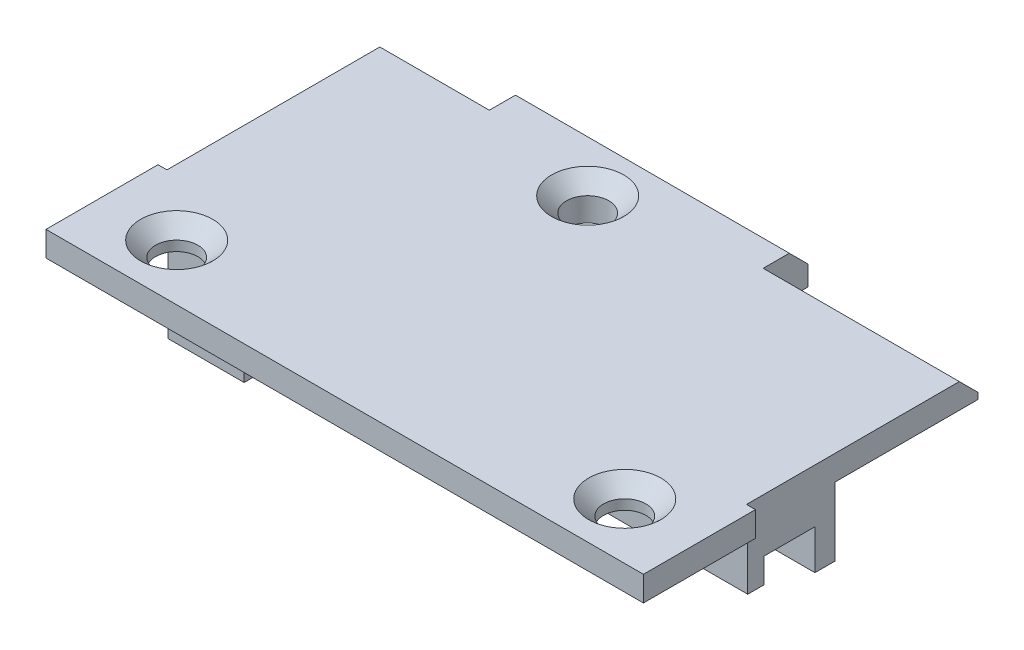
SolidWorks part; units mm, degrees
ref_plane "Front Plane" through (0, 0, 0) normal (0, 0, 1) x (1, 0, 0)
ref_plane "Top Plane" through (0, 0, 0) normal (0, 1, 0) x (1, 0, 0)
ref_plane "Right Plane" through (0, 0, 0) normal (1, 0, 0) x (0, 0, -1)
sketch "Sketch1" plane through (0, 0, 0) normal (0, 1, 0) x (1, 0, 0)
  line L0 (0, 0) -> (0, 9)
  line L1 (0, 9) -> (0.72, 9)
  line L2 (0.72, 9) -> (0.72, 27.6)
  line L3 (0.72, 27.6) -> (9.52, 27.6)
  line L4 (9.52, 27.6) -> (9.52, 29.7)
  line L5 (9.52, 29.7) -> (31.52, 29.7)
  line L6 (31.52, 29.7) -> (31.52, 27.6)
  line L7 (31.52, 27.6) -> (47.28, 27.6)
  line L8 (47.28, 27.6) -> (47.28, 9)
  line L9 (47.28, 9) -> (48, 9)
  line L10 (48, 9) -> (48, 0)
  line L11 (48, 0) -> (0, 0)
  circle A0 centre (19.42, 24.1) radius 1.7
  circle A1 centre (6, 4.5) radius 1.7
  circle A2 centre (42, 4.5) radius 1.7
  dimension "D8" = 3.4
  dimension "D1" = 48
  dimension "D2" = 9
  dimension "D3" = 0.72
  dimension "D4" = 18.6
  dimension "D5" = 2.1
  dimension "D6" = 22
  dimension "D7" = 15.76
  dimension "D9" = 24.1
  dimension "D10" = 19.42
  dimension "D11" = 4.5
  dimension "D12" = 6
  dimension "D13" = 6
  dimension "D14" = 4.5
extrude "Boss-Extrude1" add sketch "Sketch1" against normal blind 2
chamfer "Chamfer1" distance 1.5 angle 45 3 edges at (5.12, 0, -27.6) (20.52, 0, -29.7) (39.4, 0, -27.6)
chamfer "Chamfer2" distance 1.2 angle 45 3 edges at (6, 0, -2.8) (19.42, 0, -22.4) (42, 0, -2.8)
sketch "Sketch2" plane through (0, -2, 0) normal (0, -1, 0) x (1, 0, 0)
  line L0 (9.52, -28) -> (31.52, -28)
  line L1 (9.52, -29.7) -> (31.52, -29.7)
  line L2 (9.52, -29.7) -> (9.52, -28)
  line L5 (31.52, -28) -> (31.52, -29.7)
  dimension "D1" = 1.7
extrude "Boss-Extrude2" add sketch "Sketch2" along normal blind 1.1
sketch "Sketch3" plane through (0, -2, 0) normal (0, -1, 0) x (1, 0, 0)
  line L0 (19.42, -21) -> (19.42, -28) construction
  line L2 (12.42, -28) -> (12.42, -21)
  line L3 (12.42, -21) -> (26.42, -21)
  line L4 (26.42, -28) -> (26.42, -21)
  line L12 (31.52, -28) -> (9.52, -28) construction
  line L14 (12.42, -28) -> (26.42, -28)
  circle A0 centre (19.42, -24.1) radius 1.7
  circle A1 centre (19.42, -24.1) radius 1.7 construction
  dimension "D1" = 14
  dimension "D3" = 7
extrude "Boss-Extrude3" add sketch "Sketch3" along normal up to surface (1.1 mm away) up to face at (20.52, -3.1, -28.85)
sketch "Sketch4" plane through (0, -2, 0) normal (0, -1, 0) x (1, 0, 0)
  line L0 (0.72, -9.1) -> (47.28, -9.1)
  line L1 (47.28, -9.1) -> (47.28, -16.1)
  line L2 (47.28, -9) -> (47.28, -27.6) construction
  line L3 (47.28, -16.3) -> (44.08, -16.3) construction
  line L4 (44.08, -16.3) -> (44.08, -18.2)
  line L5 (44.08, -18.2) -> (42.26, -18.2)
  line L6 (42.26, -18.2) -> (42.26, -16)
  line L7 (42.26, -16) -> (38.56, -16)
  line L8 (38.56, -16) -> (38.56, -18.2)
  line L9 (38.56, -18.2) -> (35.18, -18.2)
  line L10 (35.18, -18.2) -> (35.18, -16)
  line L11 (35.18, -16) -> (31.48, -16)
  line L12 (31.48, -16) -> (31.48, -18.2)
  line L13 (31.48, -18.2) -> (30.28, -18.2)
  line L14 (30.28, -18.2) -> (30.28, -14.4)
  line L15 (30.28, -14.4) -> (26.6, -14.4)
  line L16 (26.6, -14.4) -> (26.6, -13.4)
  line L17 (26.6, -13.4) -> (11.4, -13.4)
  line L18 (11.4, -13.4) -> (11.4, -18.2)
  line L19 (11.4, -18.2) -> (10.02, -18.2)
  line L20 (10.02, -18.2) -> (10.02, -16)
  line L21 (10.02, -16) -> (6.32, -16)
  line L22 (6.32, -16) -> (6.32, -18.2)
  line L23 (6.32, -18.2) -> (3.72, -18.2)
  line L24 (3.72, -18.2) -> (3.72, -19.4)
  line L25 (3.72, -19.4) -> (0.72, -19.4)
  line L26 (0.72, -27.6) -> (0.72, -9) construction
  line L27 (0.72, -19.4) -> (0.72, -9.1)
  line L28 (47.28, -16.1) -> (44.08, -16.1)
  line L29 (44.08, -16.1) -> (44.08, -16.3)
  line L30 (48, -9) -> (47.28, -9) construction
  dimension "D1" = 3
  dimension "D2" = 2.6
  dimension "D3" = 3.7
  dimension "D4" = 1.38
  dimension "D5" = 15.2
  dimension "D6" = 20.68
  dimension "D7" = 3.7
  dimension "D8" = 3.7
  dimension "D9" = 3.2
  dimension "D10" = 1.2
  dimension "D11" = 3.38
  dimension "D12" = 0.1
  dimension "D13" = 1.9
  dimension "D14" = 3.8
  dimension "D15" = 1
  dimension "D16" = 4.8
  dimension "D17" = 2.2
  dimension "D18" = 1.2
  dimension "D19" = 0.2
  dimension "D20" = 7
  dimension "D21" = 5.02
  dimension "D22" = 2.2
  dimension "D23" = 2.2
extrude "Boss-Extrude4" add sketch "Sketch4" along normal blind 5.5
fillet "Fillet1" radius 0.5 12 edges at (42.26, -4.75, -18.2) (42.26, -4.75, -16) (35.18, -4.75, -18.2) (35.18, -4.75, -16) (38.56, -4.75, -16) (38.56, -4.75, -18.2) (31.48, -4.75, -16) (31.48, -4.75, -18.2) (10.02, -4.75, -18.2) (10.02, -4.75, -16) (6.32, -4.75, -16) (6.32, -4.75, -18.2)
sketch "Sketch5" plane through (0, -7.5, 0) normal (0, -1, 0) x (1, 0, 0)
  line L0 (0.72, -9) -> (0, -9) construction
  line L1 (0.72, -9.1) -> (6.82, -9.1)
  line L2 (0.72, -9.1) -> (0.72, -14.5)
  line L3 (0.72, -14.5) -> (6.82, -14.5)
  line L4 (6.82, -9.1) -> (6.82, -14.5)
  line L5 (47.28, -9.1) -> (0.72, -9.1) construction
  line L6 (0.72, -9.1) -> (0.72, -19.4) construction
  dimension "D1" = 5.5
  dimension "D2" = 6.1
extrude "Boss-Extrude5" add sketch "Sketch5" along normal blind 4.3
sketch "Sketch6" plane through (0, -7.5, 0) normal (0, -1, 0) x (1, 0, 0)
  line L0 (47.28, -16.1) -> (47.28, -9.1) construction
  line L1 (6.82, -9.1) -> (47.28, -9.1)
  line L2 (6.82, -9.1) -> (6.82, -14.5)
  line L3 (6.82, -14.5) -> (47.28, -14.5)
  line L4 (47.28, -9.1) -> (47.28, -14.5)
  line L5 (0.72, -14.5) -> (6.82, -14.5) construction
extrude "Cut-Extrude1" cut sketch "Sketch6" against normal blind 1.2
sketch "Sketch7" plane through (0, -6.3, 0) normal (0, -1, 0) x (1, 0, 0)
  line L0 (11.4, -13.4) -> (11.4, -13.12)
  line L1 (12.14, -12.15) -> (14.52, -11.4893)
  line L2 (23.64, -10.4) -> (47.28, -10.4)
  line L3 (47.28, -14.5) -> (47.28, -9.1) construction
  line L4 (47.28, -10.4) -> (47.28, -14.5)
  line L5 (47.28, -14.5) -> (26.6, -14.5)
  line L6 (26.6, -14.5) -> (26.6, -13.4)
  line L7 (26.6, -13.4) -> (11.4, -13.4)
  arc A0 (11.4, -13.12) -> (12.14, -12.15) centre (12.4, -13.1156) cw
  arc A1 (14.52, -11.4893) -> (23.64, -10.4) centre (23.1951, -45.3972) cw
  dimension "D5" = 1
  dimension "D6" = 35
  dimension "D1" = 23.64
  dimension "D2" = 4.1
  dimension "D3" = 0.28
  dimension "D4" = 2.47
  dimension "D7" = 0.97
  dimension "D8" = 0.74
  dimension "D9" = 2.38
extrude "Cut-Extrude2" cut sketch "Sketch7" against normal blind 2
sketch "Sketch8" plane through (0, -2, 0) normal (0, -1, 0) x (1, 0, 0)
  line L0 (26.42, -28) -> (26.42, -21) construction
  line L1 (12.42, -21) -> (26.42, -21)
  line L2 (12.42, -21) -> (12.42, -16)
  line L3 (12.42, -16) -> (26.42, -16)
  line L4 (26.42, -21) -> (26.42, -16)
  dimension "D1" = 5
extrude "Cut-Extrude3" cut sketch "Sketch8" against normal blind 1
